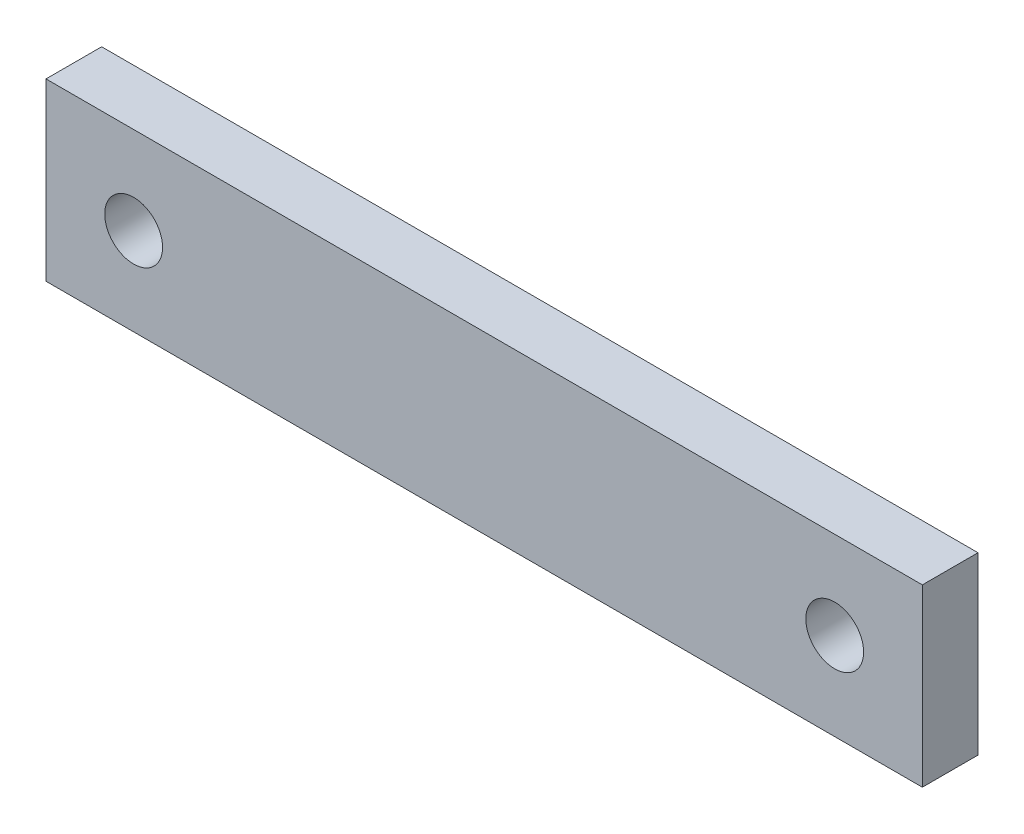
SolidWorks part; units mm, degrees
ref_plane "Front Plane" through (0, 0, 0) normal (0, 0, 1) x (1, 0, 0)
ref_plane "Top Plane" through (0, 0, 0) normal (0, 1, 0) x (1, 0, 0)
ref_plane "Right Plane" through (0, 0, 0) normal (1, 0, 0) x (0, 0, -1)
sketch "Sketch1" plane through (0, 0, 0) normal (0, 0, 1) x (1, 0, 0)
  line L1 (50, -10) -> (-50, -10)
  line L2 (50, -10) -> (50, 10)
  line L3 (50, 10) -> (-50, 10)
  line L4 (-50, -10) -> (-50, 10)
  line L5 (50, -10) -> (-50, 10) construction
  line L6 (50, 10) -> (-50, -10) construction
  line L8 (0, 10) -> (0, -10) construction
  circle A0 centre (-40, 0) radius 3.3
  circle A1 centre (40, 0) radius 3.3
  point P0 (0, 0)
  dimension "D5" = 6.6
  dimension "D1" = 20
  dimension "D2" = 100
  dimension "D3" = 10
extrude "Boss-Extrude1" add sketch "Sketch1" along normal mid plane 6.35
